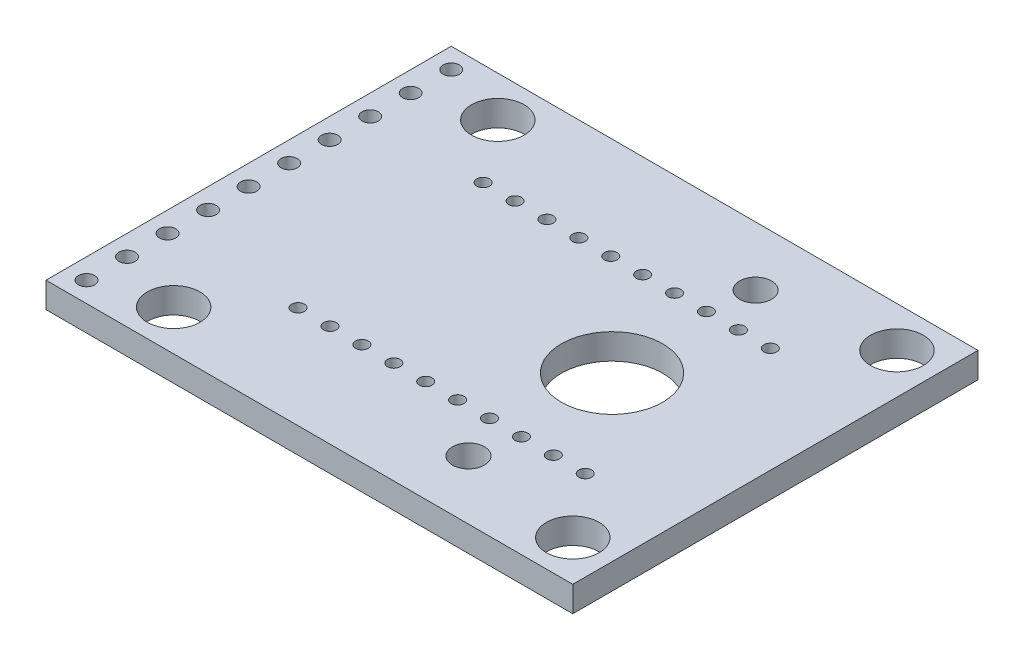
SolidWorks part; units mm, degrees
ref_plane "Front Plane" through (0, 0, 0) normal (0, 0, 1) x (1, 0, 0)
ref_plane "Top Plane" through (0, 0, 0) normal (0, 1, 0) x (1, 0, 0)
ref_plane "Right Plane" through (0, 0, 0) normal (1, 0, 0) x (0, 0, -1)
sketch "Sketch1" plane through (0, 0, 0) normal (0, 1, 0) x (1, 0, 0)
  line L0 (0, 12.7) -> (33.02, 12.7) construction
  line L1 (0, 0) -> (33.02, 0)
  line L2 (0, 0) -> (0, 25.4)
  line L3 (0, 25.4) -> (33.02, 25.4)
  line L4 (33.02, 0) -> (33.02, 25.4)
  line L5 (5.461, 22.86) -> (30.48, 22.86) construction
  line L6 (30.48, 22.86) -> (30.48, 2.54) construction
  circle A0 centre (5.461, 2.54) radius 1.651
  circle A1 centre (30.48, 2.54) radius 1.651
  circle A2 centre (30.48, 22.86) radius 1.651
  circle A3 centre (5.461, 22.86) radius 1.651
  dimension "D3" = 5.461
  dimension "D4" = 2.54
  dimension "D5" = 3.302
  dimension "D6" = 3.302
  dimension "D7" = 30.48
  dimension "D8" = 2.54
  dimension "D1" = 33.02
  dimension "D2" = 25.4
extrude "Boss-Extrude1" add sketch "Sketch1" along normal blind 1.6
sketch "Sketch2" plane through (0, 1.6, 0) normal (0, 1, 0) x (1, 0, 0)
  line L0 (17.78, 17.25) -> (17.78, 8.15) construction
  line L1 (6.505, 17.25) -> (28.805, 17.25) construction
  line L2 (6.505, 17.25) -> (6.505, 8.15) construction
  line L3 (6.505, 8.15) -> (28.805, 8.15) construction
  line L4 (28.805, 17.25) -> (28.805, 8.15) construction
  line L5 (6.505, 12.7) -> (28.805, 12.7) construction
  line L6 (0, 25.4) -> (0, 0) construction
  line L7 (0, 0) -> (33.02, 0) construction
  circle A0 centre (22.78, 12.7) radius 3.175
  circle A1 centre (27.4, 6.4) radius 0.4
  circle A2 centre (25.4, 6.4) radius 0.4
  circle A3 centre (23.4, 6.4) radius 0.4
  circle A4 centre (21.4, 6.4) radius 0.4
  circle A5 centre (19.4, 6.4) radius 0.4
  circle A6 centre (17.4, 6.4) radius 0.4
  circle A7 centre (15.4, 6.4) radius 0.4
  circle A8 centre (13.4, 6.4) radius 0.4
  circle A9 centre (11.4, 6.4) radius 0.4
  circle A10 centre (9.4, 6.4) radius 0.4
  circle A11 centre (26.4, 19) radius 0.4
  circle A12 centre (24.4, 19) radius 0.4
  circle A13 centre (22.4, 19) radius 0.4
  circle A14 centre (20.4, 19) radius 0.4
  circle A15 centre (18.4, 19) radius 0.4
  circle A16 centre (16.4, 19) radius 0.4
  circle A17 centre (14.4, 19) radius 0.4
  circle A18 centre (12.4, 19) radius 0.4
  circle A19 centre (10.4, 19) radius 0.4
  circle A20 centre (8.4, 19) radius 0.4
  circle A21 centre (22.78, 3.7) radius 1
  circle A22 centre (22.78, 21.7) radius 1
  dimension "D5" = 6.35
  dimension "D6" = 5
  dimension "D9" = 9.62
  dimension "D10" = 6.3
  dimension "D11" = 0.8
  dimension "D13" = 0.8
  dimension "D14" = 6.3
  dimension "D15" = 8.62
  dimension "D17" = 9
  dimension "D18" = 5
  dimension "D19" = 2
  dimension "D20" = 2
  dimension "D21" = 9
  dimension "D22" = 5
  dimension "D1" = 22.3
  dimension "D2" = 9.1
  dimension "D3" = 11.275
  dimension "D4" = 11.025
  dimension "D7" = 17.78
  dimension "D8" = 12.7
  dimension "D12" = 10
  dimension "D16" = 10
extrude "Cut-Extrude1" cut sketch "Sketch2" against normal through all
sketch "Sketch3" plane through (0, 1.6, 0) normal (0, 1, 0) x (1, 0, 0)
  line L0 (0, 0) -> (33.02, 0) construction
  line L1 (0, 25.4) -> (0, 0) construction
  circle A0 centre (1.27, 1.27) radius 0.508
  circle A1 centre (1.27, 3.81) radius 0.508
  circle A2 centre (1.27, 6.35) radius 0.508
  circle A3 centre (1.27, 8.89) radius 0.508
  circle A4 centre (1.27, 11.43) radius 0.508
  circle A5 centre (1.27, 13.97) radius 0.508
  circle A6 centre (1.27, 16.51) radius 0.508
  circle A7 centre (1.27, 19.05) radius 0.508
  circle A8 centre (1.27, 21.59) radius 0.508
  circle A9 centre (1.27, 24.13) radius 0.508
  dimension "D1" = 1.27
  dimension "D2" = 1.27
  dimension "D3" = 1.016
  dimension "D4" = 10
extrude "Cut-Extrude2" cut sketch "Sketch3" against normal through all
equation "\"1.3inch\"=75.3367"
